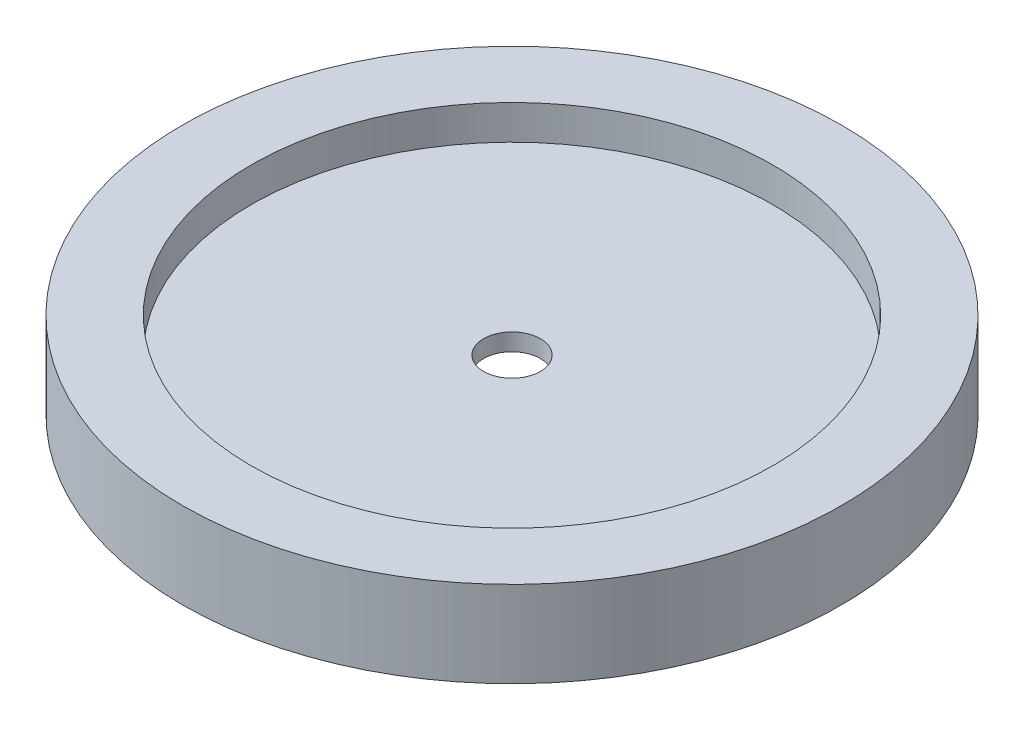
SolidWorks part; units mm, degrees
ref_plane "Front Plane" through (0, 0, 0) normal (0, 0, 1) x (1, 0, 0)
ref_plane "Top Plane" through (0, 0, 0) normal (0, 1, 0) x (1, 0, 0)
ref_plane "Right Plane" through (0, 0, 0) normal (1, 0, 0) x (0, 0, -1)
sketch "Sketch1" plane through (0, 0, 0) normal (0, 1, 0) x (1, 0, 0)
  circle A0 centre (0, 0) radius 7.575
  circle A1 centre (0, 0) radius 9.575
  dimension "D1" = 15.15
  dimension "D2" = 2
extrude "Boss-Extrude1" add sketch "Sketch1" along normal blind 1
sketch "Sketch2" plane through (0, 0, 0) normal (0, -1, 0) x (1, 0, 0)
  circle A0 centre (0, 0) radius 9.575 construction
  circle A1 centre (0, 0) radius 9.575
extrude "Boss-Extrude2" add sketch "Sketch2" along normal blind 1.5
sketch "Sketch3" plane through (0, -1.5, 0) normal (0, -1, 0) x (1, 0, 0)
  circle A0 centre (0, 0) radius 2.575
  dimension "D1" = 5.15
extrude "Cut-Extrude1" cut sketch "Sketch3" against normal blind 1
chamfer "Chamfer1" distance 0.2 angle 45 1 edges at (0, -1.5, -2.575)
chamfer "Chamfer2" [suppressed] distance 0.2 angle 45
sketch "Sketch4" plane through (0, -0.5, 0) normal (0, -1, 0) x (1, 0, 0)
  circle A0 centre (0, 0) radius 0.825
  dimension "D1" = 1.65
extrude "Cut-Extrude2" cut sketch "Sketch4" against normal through all
